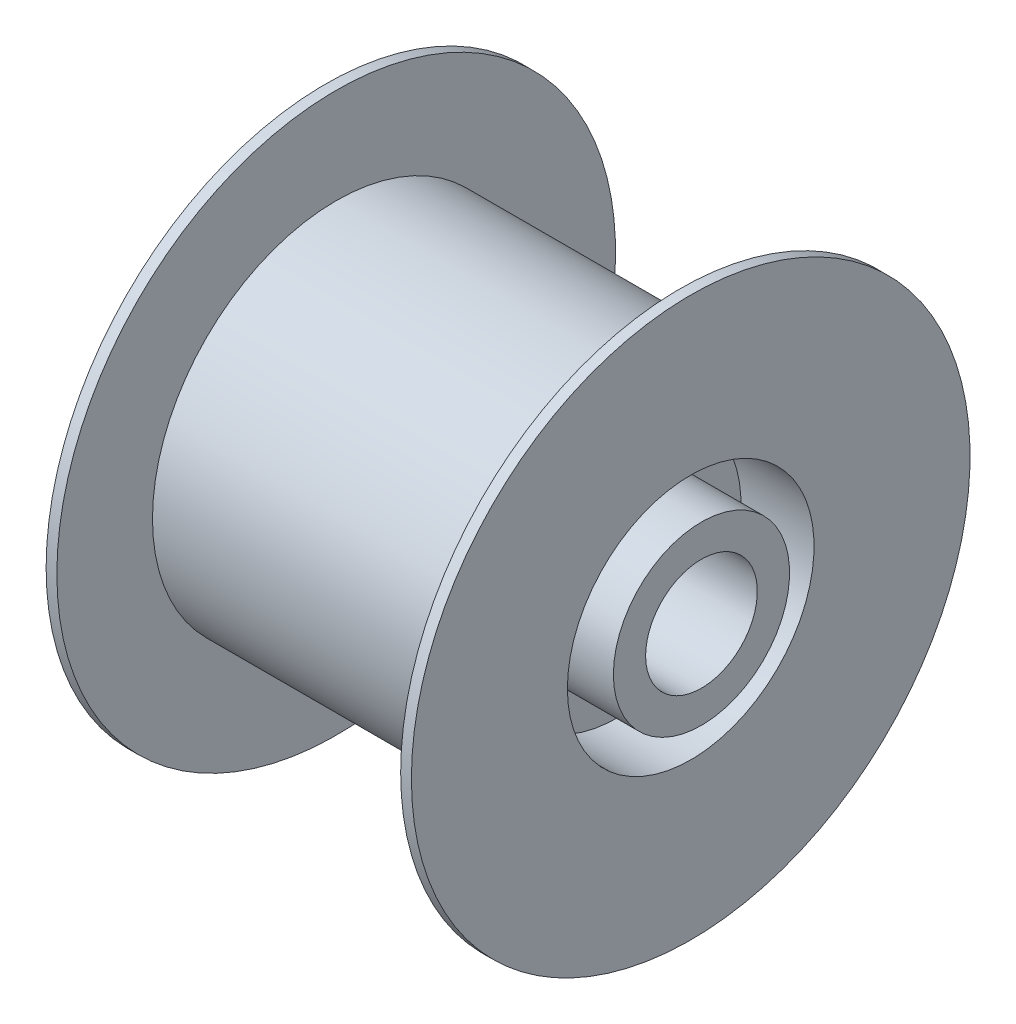
SolidWorks part; units mm, degrees
material "SUS304"
ref_plane "Front Plane" through (0, 0, 0) normal (0, 0, 1) x (1, 0, 0)
ref_plane "Top Plane" through (0, 0, 0) normal (0, 1, 0) x (1, 0, 0)
ref_plane "Right Plane" through (0, 0, 0) normal (1, 0, 0) x (0, 0, -1)
ref_plane "Plane1" through (9, 0, 0) normal (1, 0, 0) x (0, 0, -1)
sketch "Sketch1" plane through (0, 0, 0) normal (0, 0, 1) x (1, 0, 0)
  line L0 (0, 0) -> (18, 0) construction
  line L1 (0, 4.1) -> (0, 2.6)
  line L2 (0, 2.6) -> (18, 2.6)
  line L3 (18, 2.6) -> (18, 4.1)
  line L4 (18, 4.1) -> (14.1, 4.1)
  line L5 (3.9, 4.1) -> (3.9, 5.74)
  line L6 (14.1, 4.1) -> (14.1, 5.74)
  line L7 (3.9, 4.1) -> (0, 4.1)
  line L8 (0.5, 5.74) -> (0.5, 13)
  line L9 (0.5, 13) -> (1, 13)
  line L10 (1, 13) -> (1, 8.55)
  line L11 (1, 8.55) -> (17, 8.55)
  line L12 (17, 8.55) -> (17, 13)
  line L13 (17, 13) -> (17.5, 13)
  line L14 (17.5, 13) -> (17.5, 5.74)
  line L15 (0, 0) -> (0, 13) construction
  line L16 (0, 13) -> (0.5, 13) construction
  line L17 (18, 4.1) -> (18, 13) construction
  line L18 (18, 13) -> (17.5, 13) construction
  line L19 (14.1, 5.74) -> (17.5, 5.74)
  line L20 (0.5, 5.74) -> (3.9, 5.74)
  dimension "L" = 18
  dimension "D1." = 8.2
  dimension "V" = 5.2
  dimension "MSM_4" = 3.9
  dimension "D" = 26
  dimension "L_s" = 17
  dimension "MSM_2" = 1.64
  dimension "MSM_3" = 0.5
  dimension "MSM_1" = 17.1
revolve "Revolve1" add sketch "Sketch1" angle 360 about L0
equation "\"FIX_1@Plane1\"= \"L@Sketch1\" * 0.5"
